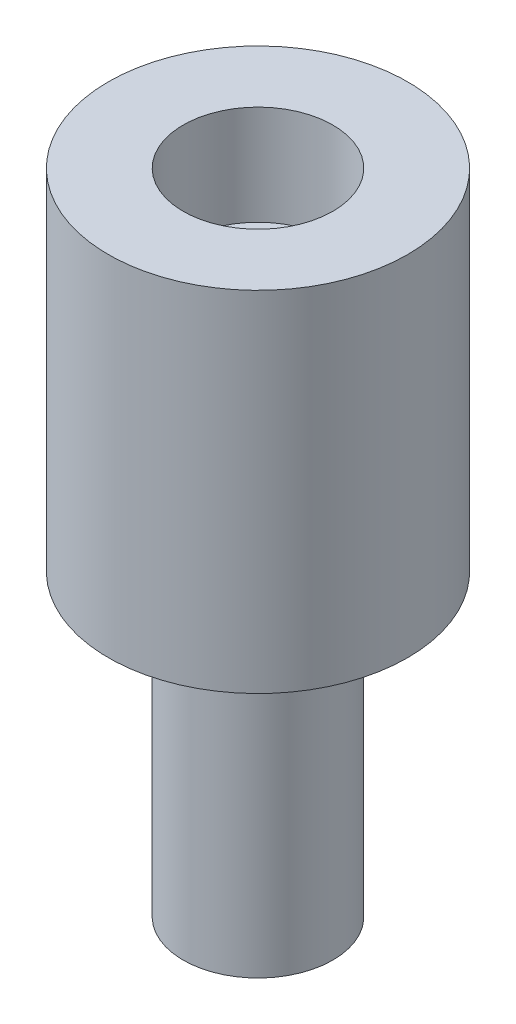
SolidWorks part; units mm, degrees
ref_plane "Front Plane" through (0, 0, 0) normal (0, 0, 1) x (1, 0, 0)
ref_plane "Top Plane" through (0, 0, 0) normal (0, 1, 0) x (1, 0, 0)
ref_plane "Right Plane" through (0, 0, 0) normal (1, 0, 0) x (0, 0, -1)
sketch "Sketch1" plane through (0, 0, 0) normal (0, 0, 1) x (1, 0, 0)
  line L0 (0, 11) -> (-1.5, 11)
  line L1 (-1.5, 11) -> (-1.5, 13)
  line L2 (-1.5, 13) -> (-3, 13)
  line L3 (-3, 13) -> (-3, 6)
  line L4 (-3, 6) -> (-1.5, 6)
  line L5 (-1.5, 6) -> (-1.5, 0)
  line L6 (-1.5, 0) -> (0, 0)
  line L7 (0, 0) -> (0, 11)
  dimension "D1" = 1.5
  dimension "D2" = 2
  dimension "D3" = 6
  dimension "D4" = 7
  dimension "D5" = 3
revolve "Revolve1" add sketch "Sketch1" angle 360 about L7
